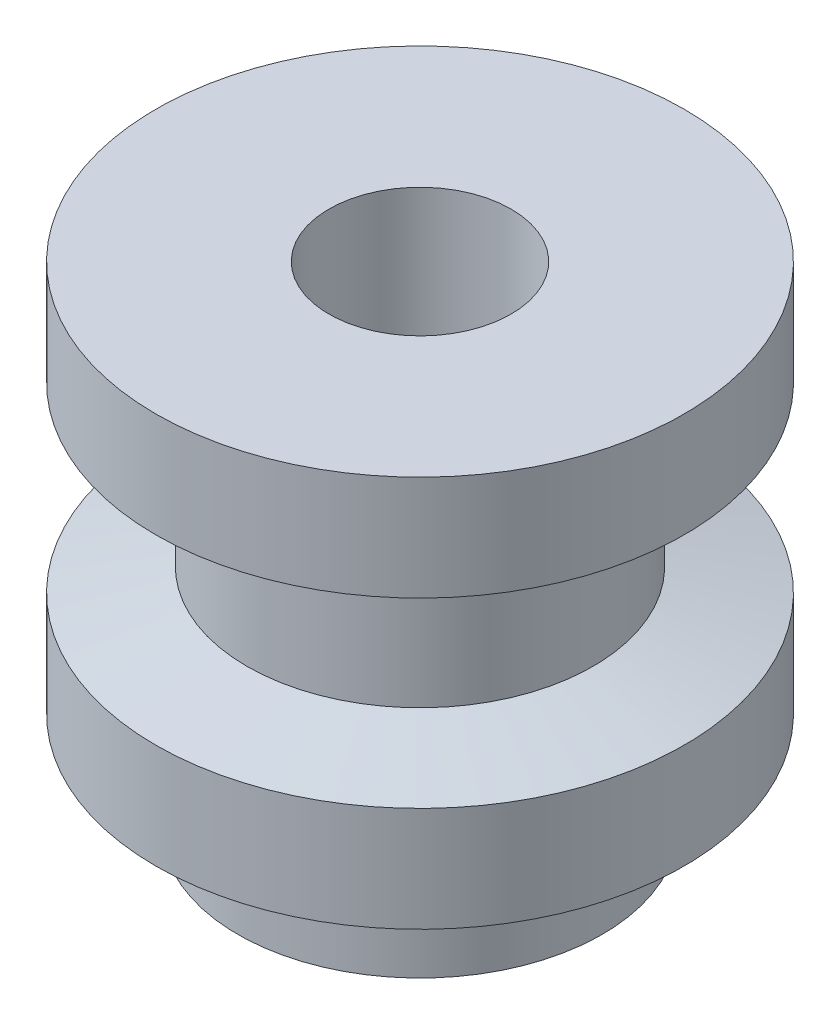
SolidWorks part; units mm, degrees
material "Nylon 6/10"
ref_plane "Front Plane" through (0, 0, 0) normal (0, 0, 1) x (1, 0, 0)
ref_plane "Top Plane" through (0, 0, 0) normal (0, 1, 0) x (1, 0, 0)
ref_plane "Right Plane" through (0, 0, 0) normal (1, 0, 0) x (0, 0, -1)
sketch "Sketch1" plane through (0, 0, 0) normal (1, 0, 0) x (0, 0, -1)
  line L0 (-1, 0) -> (-1, 5.4)
  line L1 (-1, 5.4) -> (-2.9, 5.4)
  line L2 (-2.9, 5.4) -> (-2.9, 4.25)
  line L3 (-2.9, 4.25) -> (-1.9, 4)
  line L4 (-1.9, 4) -> (-1.9, 2.5)
  line L5 (-1.9, 2.5) -> (-2.9, 2.25)
  line L6 (-2.9, 2.25) -> (-2.9, 1.1)
  line L7 (-2.9, 1.1) -> (-2, 1.1)
  line L8 (-2, 1.1) -> (-2, 0)
  line L9 (-2, 0) -> (-1, 0)
  line L10 (0, 0) -> (0, 6.655) construction
  point P10 (-1.9, 3.25)
  dimension "D1" = 1
  dimension "D2" = 5.4
  dimension "D3" = 2.9
  dimension "D4" = 1.9
  dimension "D5" = 4.3
  dimension "D6" = 2
  dimension "D7" = 1.5
  dimension "D8" = 2
revolve "Revolve1" add sketch "Sketch1" angle 360 about L10
ref_plane "Plane1" through (0, 3.25, 1.9) normal (0, 1, 0) x (1, 0, 0)
move or copy body "Body-Move/Copy1" [suppressed] bodies to move or copy 101
